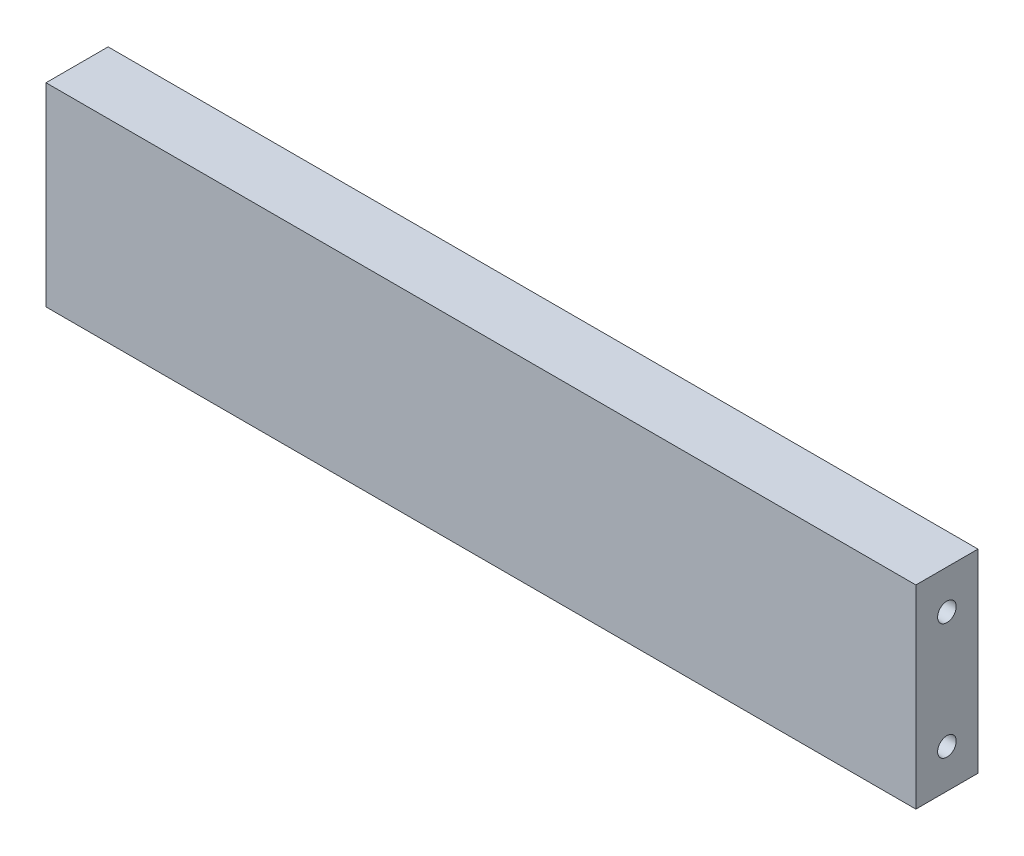
SolidWorks part; units mm, degrees
ref_plane "Plan1" through (0, 0, 0) normal (0, 0, 1) x (1, 0, 0)
ref_plane "Plan2" through (0, 0, 0) normal (0, 1, 0) x (1, 0, 0)
ref_plane "Plan3" through (0, 0, 0) normal (1, 0, 0) x (0, 0, -1)
sketch "Esquisse1" plane through (0, 0, 0) normal (0, 0, 1) x (1, 0, 0)
  line L0 (0, 0) -> (112, 0)
  line L1 (0, 0) -> (0, 25)
  line L2 (112, 25) -> (0, 25)
  line L3 (112, 25) -> (112, 0)
  dimension "D1" = 25
  dimension "D2" = 112
extrude "Base-Extrusion" add sketch "Esquisse1" along normal blind 8
sketch "Esquisse2" plane through (112, 0, 0) normal (1, 0, 0) x (0, 0, -1)
  line L0 (-4, 25) -> (-4, 0) construction
  line L1 (-8, 0) -> (0, 0) construction
  line L2 (-8, 25) -> (0, 25) construction
  circle A0 centre (-4, 20) radius 1.2
  circle A1 centre (-4, 5) radius 1.2
  dimension "D3" = 2.4
  dimension "D1" = 15
  dimension "D2" = 5
extrude "Enlèv. mat.-Extru.1" cut sketch "Esquisse2" against normal blind 11
sketch "Esquisse3" plane through (0, 0, 0) normal (-1, 0, 0) x (0, 0, 1)
  line L0 (4, 27) -> (4, -1) construction
  line L3 (8, 25) -> (0, 25) construction
  circle A0 centre (4, 20) radius 1.2
  circle A1 centre (4, 5) radius 1.2
  dimension "D2" = 2.4
  dimension "D3" = 5
  dimension "D4" = 15
extrude "Enlèv. mat.-Extru.2" cut sketch "Esquisse3" against normal blind 11
cosmetic thread "Représentation de filetage1" parameters "D1"=8, "D2"=3
cosmetic thread "Représentation de filetage2" parameters "D1"=8, "D2"=3
